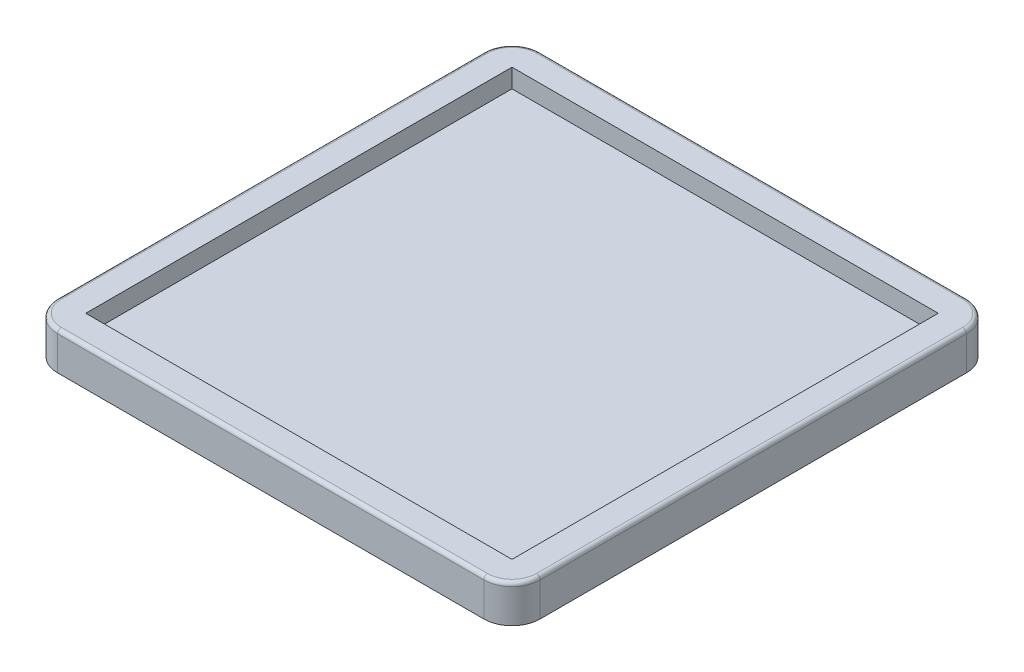
SolidWorks part; units mm, degrees
ref_plane "Front Plane" through (0, 0, 0) normal (0, 0, 1) x (1, 0, 0)
ref_plane "Top Plane" through (0, 0, 0) normal (0, 1, 0) x (1, 0, 0)
ref_plane "Right Plane" through (0, 0, 0) normal (1, 0, 0) x (0, 0, -1)
sketch "Sketch1" plane through (0, 0, 0) normal (0, 1, 0) x (1, 0, 0)
  line L1 (-64.25, 64.25) -> (64.25, 64.25)
  line L2 (-64.25, 64.25) -> (-64.25, -64.25)
  line L3 (-64.25, -64.25) -> (64.25, -64.25)
  line L4 (64.25, 64.25) -> (64.25, -64.25)
  line L5 (-64.25, 64.25) -> (64.25, -64.25) construction
  line L6 (-64.25, -64.25) -> (64.25, 64.25) construction
  point P0 (0, 0)
  dimension "D1" = 128.5
  dimension "D2" = 128.5
extrude "Boss-Extrude1" add sketch "Sketch1" along normal blind 10
sketch "Sketch2" plane through (0, 10, 0) normal (0, 1, 0) x (1, 0, 0)
  line L1 (-56.75, 56.75) -> (56.75, 56.75)
  line L2 (-56.75, 56.75) -> (-56.75, -56.75)
  line L3 (-56.75, -56.75) -> (56.75, -56.75)
  line L4 (56.75, 56.75) -> (56.75, -56.75)
  line L5 (-56.75, 56.75) -> (56.75, -56.75) construction
  line L6 (-56.75, -56.75) -> (56.75, 56.75) construction
  point P0 (0, 0)
  dimension "D1" = 113.5
  dimension "D2" = 113.5
extrude "Cut-Extrude3" cut sketch "Sketch2" against normal blind 5
fillet "Fillet1" radius 7.5 4 edges at (64.25, 5, 64.25) (64.25, 5, -64.25) (-64.25, 5, -64.25) (-64.25, 5, 64.25)
fillet "Fillet2" radius 1 8 edges at (-62.0533, 10, -62.0533) (0, 10, -64.25) (62.0533, 10, -62.0533) (64.25, 10, 0) (62.0533, 10, 62.0533) (0, 10, 64.25) (-62.0533, 10, 62.0533) (-64.25, 10, 0)
equation "\"Square Width\" = 7.5mm"
equation "\"Square Height\"= 7.5mm"
equation "\"Tolerance\"= 1mm"
equation "\"D1@Sketch1\"=\"Square Width\"*15 + \"Tolerance\" + \"Square Width\"*2"
equation "\"D2@Sketch1\"=\"Square Height\"*15 + \"Tolerance\" +\"Square Height\"*2"
equation "\"Block Height\" = 5mm"
equation "\"D1@Boss-Extrude1\"=\"Base Height\""
equation "\"D1@Sketch2\"=\"Square Width\"*15 + \"Tolerance\""
equation "\"D2@Sketch2\"=\"Square Height\"*15 + \"Tolerance\""
equation "\"Base Height\"= 10mm"
equation "\"D1@Cut-Extrude3\"=\"Block Height\""
